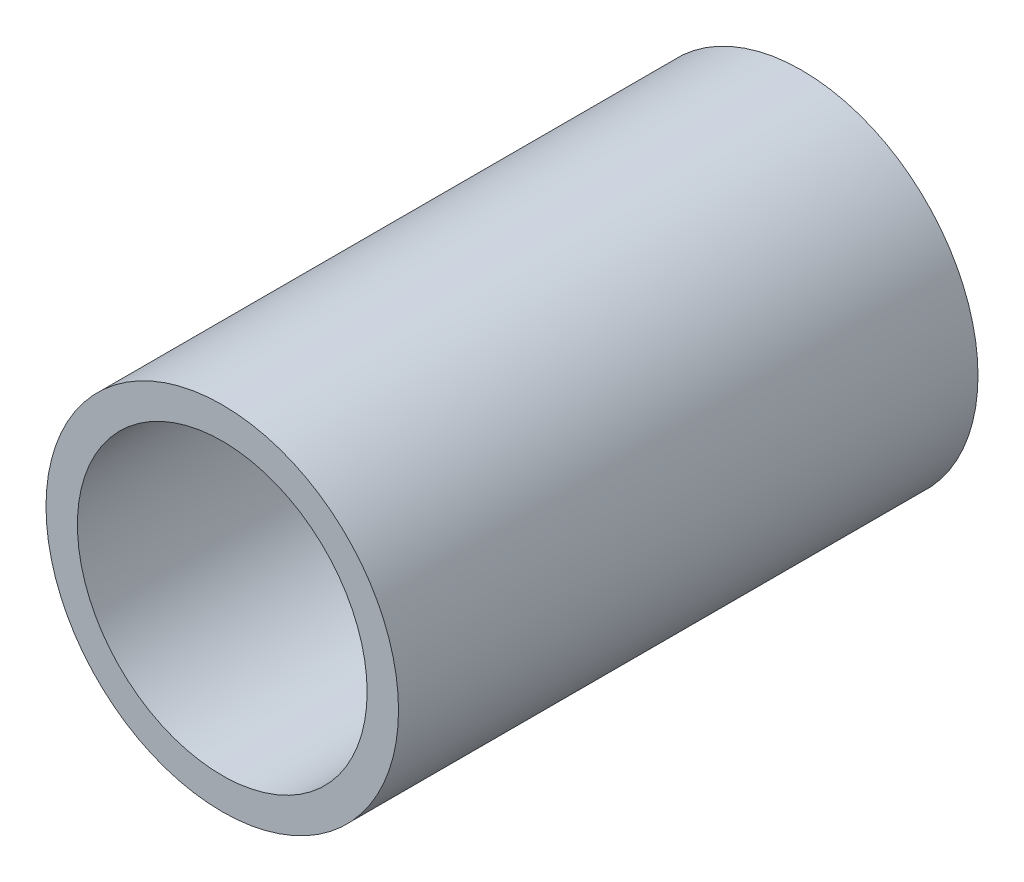
SolidWorks part; units mm, degrees
ref_plane "Front" through (0, 0, 0) normal (0, 0, 1) x (1, 0, 0)
ref_plane "Top" through (0, 0, 0) normal (0, 1, 0) x (1, 0, 0)
ref_plane "Right" through (0, 0, 0) normal (1, 0, 0) x (0, 0, -1)
sketch "Эскиз1" plane through (0, 0, 0) normal (0, 0, 1) x (1, 0, 0)
  circle A0 centre (0, 0) radius 3
  circle A1 centre (0, 0) radius 3.65
  dimension "D1" = 7.3
  dimension "D2" = 6
extrude "Бобышка-Вытянуть1" add sketch "Эскиз1" along normal blind 12
